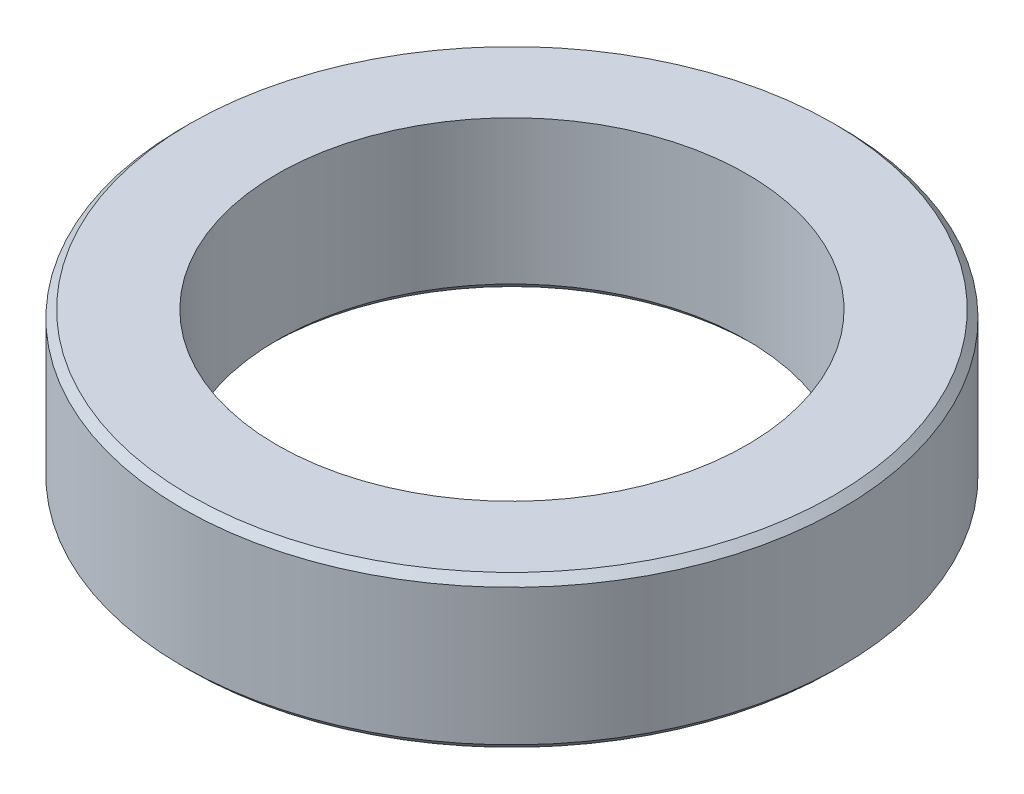
SolidWorks part; units mm, degrees
ref_plane "Front Plane" through (0, 0, 0) normal (0, 0, 1) x (1, 0, 0)
ref_plane "Top Plane" through (0, 0, 0) normal (0, 1, 0) x (1, 0, 0)
ref_plane "Right Plane" through (0, 0, 0) normal (1, 0, 0) x (0, 0, -1)
sketch "Sketch1" plane through (0, 0, 0) normal (0, 1, 0) x (1, 0, 0)
  circle A0 centre (0, 0) radius 78.74
  circle A1 centre (0, 0) radius 110.49
  dimension "D1" = 157.48
  dimension "D2" = 31.75
extrude "Boss-Extrude1" add sketch "Sketch1" along normal blind 50.8
chamfer "Chamfer1" distance 2.54 angle 45 3 edges at (0, 50.8, 110.49) (0, 0, 110.49) (0, 0, 78.74)
equation "\"shoulder offset\"= 1.25"
equation "\"ID\"=6.17"
equation "\"L\"= 2"
equation "\"D1@Sketch1\"=\"ID\"+\"ID offset\""
equation "\"D2@Sketch1\"=\"shoulder offset\""
equation "\"D1@Boss-Extrude1\"=\"L\""
equation "\"ID offset\" = 0.03"
